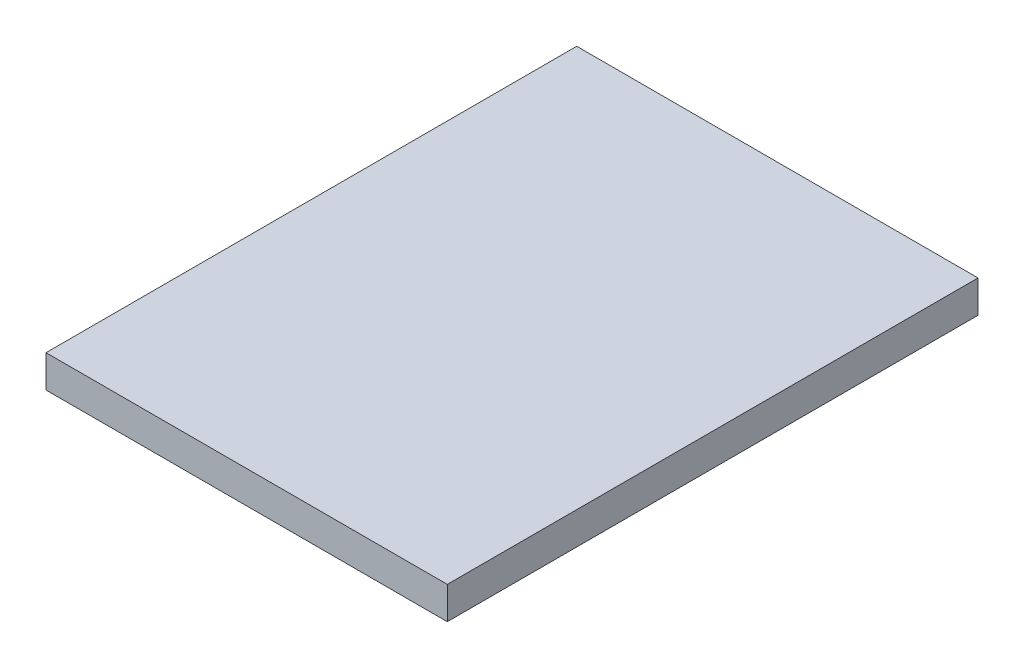
SolidWorks part; units mm, degrees
material "1.0553 (S355J0)"
ref_plane "Front Plane" through (0, 0, 0) normal (0, 0, 1) x (1, 0, 0)
ref_plane "Top Plane" through (0, 0, 0) normal (0, 1, 0) x (1, 0, 0)
ref_plane "Right Plane" through (0, 0, 0) normal (1, 0, 0) x (0, 0, -1)
sketch "Sketch1" plane through (0, 0, 0) normal (0, 1, 0) x (1, 0, 0)
  line L1 (-155, 0) -> (155, 0)
  line L2 (-155, 0) -> (-155, 410)
  line L3 (-155, 410) -> (155, 410)
  line L4 (155, 0) -> (155, 410)
  dimension "D1" = 310
  dimension "D2" = 410
extrude "Boss-Extrude1" add sketch "Sketch1" against normal blind 25
